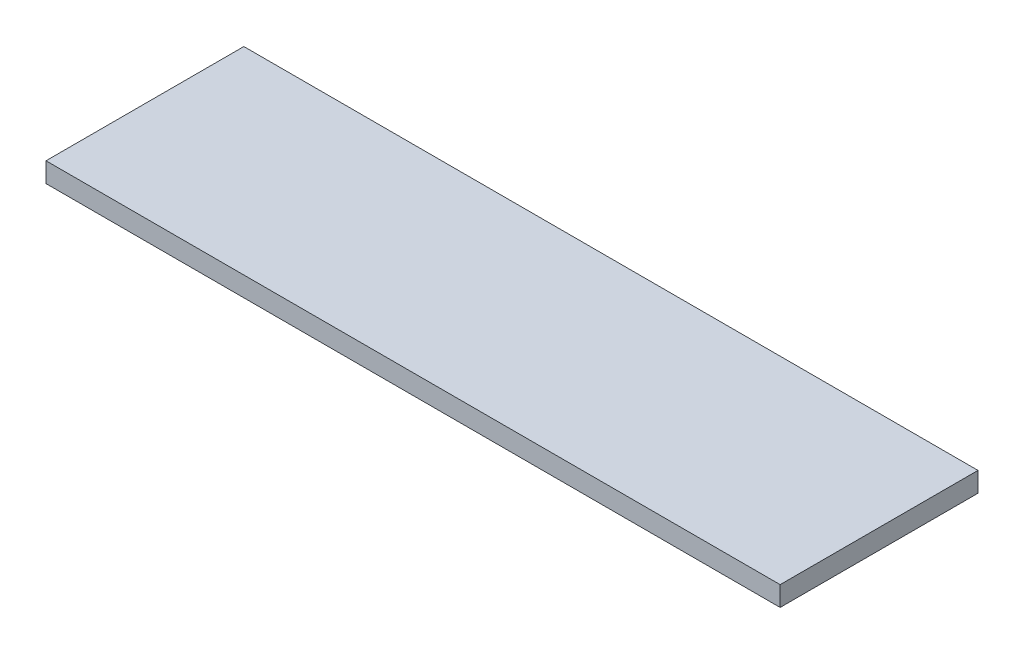
SolidWorks part; units mm, degrees
material "AISI 1020"
ref_plane "Front Plane" through (0, 0, 0) normal (0, 0, 1) x (1, 0, 0)
ref_plane "Top Plane" through (0, 0, 0) normal (0, 1, 0) x (1, 0, 0)
ref_plane "Right Plane" through (0, 0, 0) normal (1, 0, 0) x (0, 0, -1)
sketch "Sketch1" plane through (0, 0, 0) normal (0, 1, 0) x (1, 0, 0)
  line L1 (-150.6285, -16.5202) -> (99.3715, -16.5202)
  line L2 (-150.6285, -16.5202) -> (-150.6285, -56.5202)
  line L3 (-150.6285, -56.5202) -> (99.3715, -56.5202)
  line L4 (99.3715, -16.5202) -> (99.3715, -56.5202)
  dimension "D1" = 40
  dimension "D2" = 250
extrude "Boss-Extrude1" add sketch "Sketch1" along normal blind 4
sketch "Sketch4" plane through (0, 0, 0) normal (0, -1, 0) x (1, 0, 0)
  line L0 (-46.0498, 6.5202) -> (-46.0498, 206.5202) construction
  line L1 (-49.0498, 61.5878) -> (-175.9977, 61.5878)
  line L2 (-49.0498, 61.5878) -> (-49.0498, 8.3297)
  line L3 (-49.0498, 8.3297) -> (-175.9977, 8.3297)
  line L4 (-175.9977, 61.5878) -> (-175.9977, 8.3297)
  dimension "D1" = 3
extrude "Cut-Extrude3" cut sketch "Sketch4" against normal blind 10
